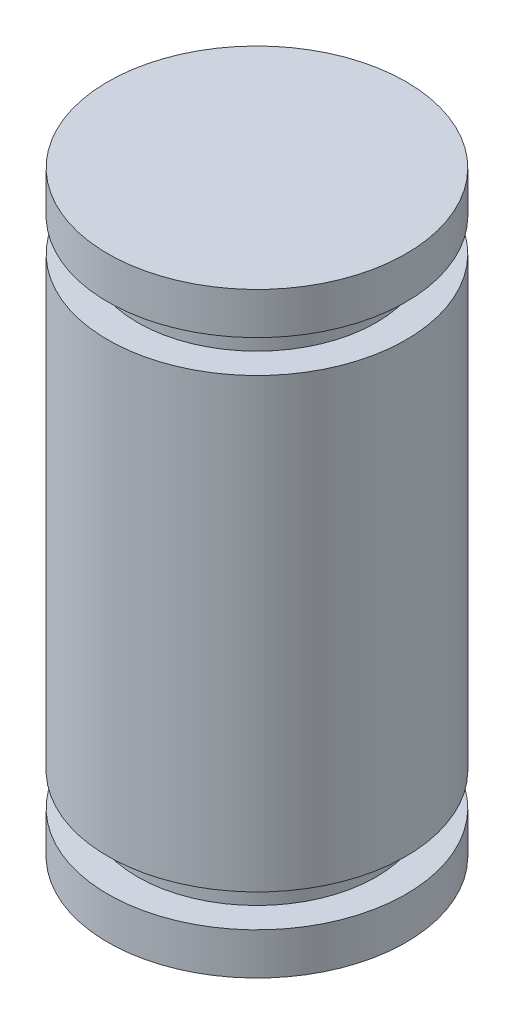
SolidWorks part; units mm, degrees
ref_plane "前视基准面" through (0, 0, 0) normal (0, 0, 1) x (1, 0, 0)
ref_plane "上视基准面" through (0, 0, 0) normal (0, 1, 0) x (1, 0, 0)
ref_plane "右视基准面" through (0, 0, 0) normal (1, 0, 0) x (0, 0, -1)
sketch "草图1" plane through (0, 0, 0) normal (0, 0, 1) x (1, 0, 0)
  line L0 (0, 0) -> (0, 20) construction
  line L1 (0, 0) -> (-5, 0)
  line L2 (-5, 0) -> (-5, 1.4)
  line L3 (-5, 1.4) -> (-4, 1.4)
  line L4 (-4, 1.4) -> (-4, 2.5)
  line L5 (-4, 2.5) -> (-5, 2.5)
  line L6 (-5, 2.5) -> (-5, 17.5)
  line L7 (-5, 17.5) -> (-4, 17.5)
  line L8 (-4, 17.5) -> (-4, 18.6)
  line L9 (-4, 18.6) -> (-5, 18.6)
  line L10 (-5, 18.6) -> (-5, 20)
  line L11 (-5, 20) -> (0, 20)
  line L12 (0, 0) -> (0, 20)
  dimension "D1" = 15
  dimension "D2" = 20
  dimension "D3" = 1.1
  dimension "D4" = 1.1
  dimension "D5" = 1
  dimension "D6" = 5
  dimension "D7" = 5
  dimension "D8" = 5
revolve "旋转1" add sketch "草图1" angle 360 about L0
